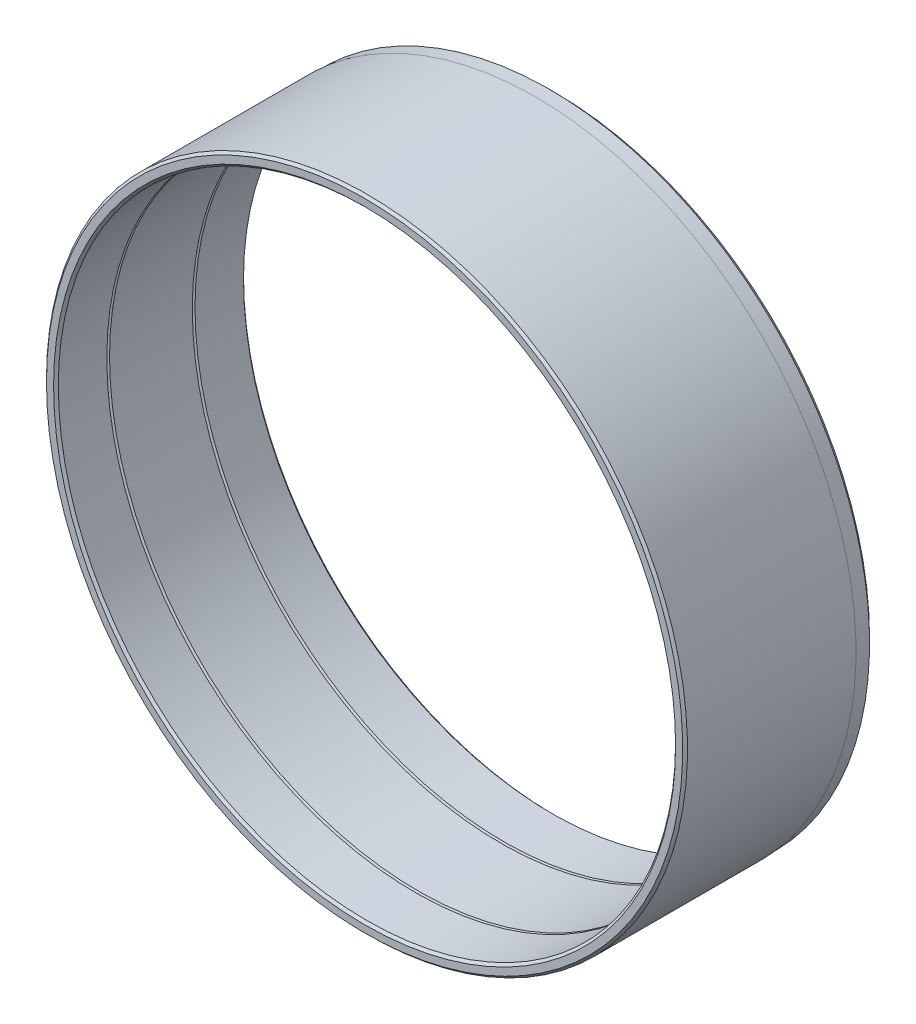
SolidWorks part; units mm, degrees
material "Phosphor bronze 10% D, UNS C52400"
ref_plane "Front Plane" through (0, 0, 0) normal (0, 0, 1) x (1, 0, 0)
ref_plane "Top Plane" through (0, 0, 0) normal (0, 1, 0) x (1, 0, 0)
ref_plane "Right Plane" through (0, 0, 0) normal (1, 0, 0) x (0, 0, -1)
sketch "Sketch1" plane through (0, 0, 0) normal (1, 0, 0) x (0, 0, -1)
  line L0 (0, 0) -> (-40, 0)
  line L1 (-4, 67.5) -> (-39.5, 67.5)
  line L2 (-40, 67) -> (-40, 0)
  line L3 (-4, 67.5) -> (-4, 67.35)
  line L4 (-1, 67.35) -> (-4, 67.35)
  line L5 (0, 67.5) -> (-40, 67.5) construction
  line L6 (0, 0) -> (0, 66.35)
  line L7 (0, 67.35) -> (-40, 67.35) construction
  line L8 (-4, 67.5) -> (-4, 0) construction
  line L9 (0, 66.35) -> (-1, 67.35)
  line L10 (-40, 67.5) -> (-40, 0) construction
  line L11 (-39.5, 67.5) -> (-40, 67)
  dimension "D1" = 40
  dimension "D2" = 67.5
  dimension "D3" = 67.35
  dimension "D4" = 4
  dimension "D5" = 1
  dimension "D6" = 45
  dimension "D7" = 0.5
  dimension "D8" = 45
revolve "Revolve1" add sketch "Sketch1" angle 360 about L0
sketch "Sketch2" plane through (0, 0, 0) normal (1, 0, 0) x (0, 0, -1)
  line L0 (0, 0) -> (-40, 0)
  line L2 (-40, 67) -> (-40, -67) construction
  line L3 (0, 65) -> (-10.7113, 65)
  line L5 (-40, 65) -> (-40, 0)
  line L6 (0, 65) -> (0, 0)
  line L7 (-29, 65.5) -> (-29, 65) construction
  line L8 (-11, 65.5) -> (-11, 65) construction
  line L9 (-29, 65) -> (-29, 0) construction
  line L10 (-11, 65) -> (-11, 0) construction
  line L11 (-29, 65.5) -> (-29.2887, 65)
  line L12 (-29, 65.5) -> (-28.7113, 65)
  line L13 (-11, 65.5) -> (-11.2887, 65)
  line L14 (-11, 65.5) -> (-10.7113, 65)
  line L15 (-29.2887, 65) -> (-40, 65)
  line L16 (-11.2887, 65) -> (-28.7113, 65)
  line L17 (0, 65) -> (-40, 65) construction
  dimension "D1" = 60
  dimension "D2" = 60
  dimension "D3" = 30
  dimension "D4" = 30
  dimension "D5" = 65
  dimension "D6" = 65.5
  dimension "D7" = 65.5
  dimension "D8" = 11
  dimension "D9" = 11
revolve "Cut-Revolve1" cut sketch "Sketch2" angle 360 about L0
chamfer "Chamfer1" distance 0.5 angle 45 2 edges at (-65, 0, 0) (-65, 0, 40)
